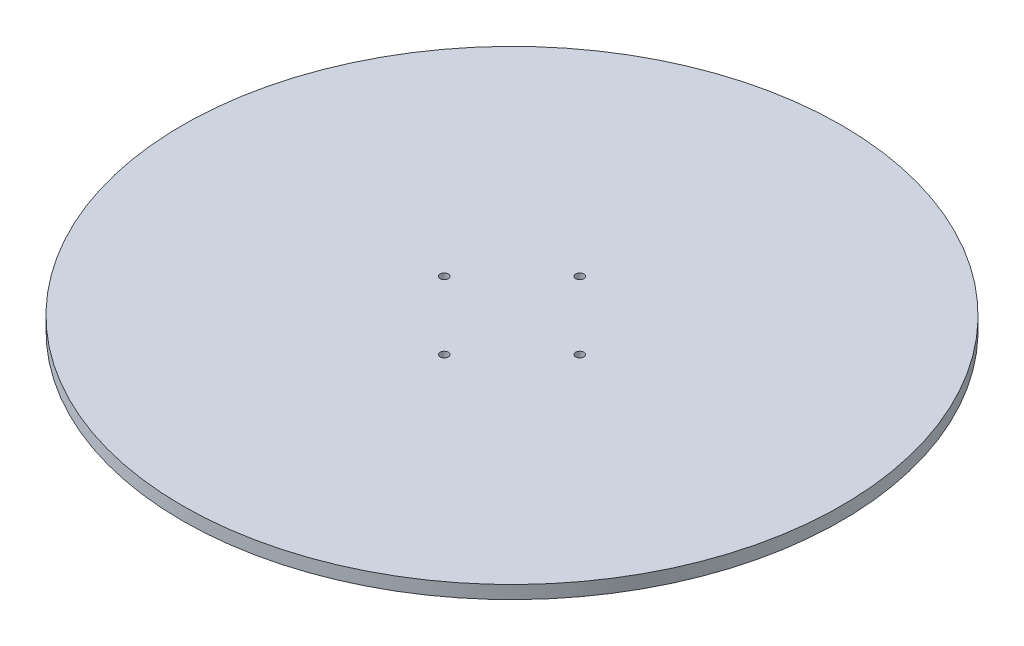
SolidWorks part; units mm, degrees
ref_plane "Front Plane" through (0, 0, 0) normal (0, 0, 1) x (1, 0, 0)
ref_plane "Top Plane" through (0, 0, 0) normal (0, 1, 0) x (1, 0, 0)
ref_plane "Right Plane" through (0, 0, 0) normal (1, 0, 0) x (0, 0, -1)
sketch "Sketch1" plane through (0, 0, 0) normal (0, 1, 0) x (1, 0, 0)
  line L5 (-40, -40) -> (40, 40) construction
  line L6 (-40, 40) -> (40, -40) construction
  circle A0 centre (0, 0) radius 80
  point P0 (0, 0)
  dimension "D3" = 160
  dimension "D1" = 80
  dimension "D2" = 80
extrude "Boss-Extrude1" add sketch "Sketch1" along normal mid plane 3.175
sketch "Sketch2" plane through (0, -1.5875, 0) normal (0, -1, 0) x (1, 0, 0)
  circle A0 centre (-16.45, 0) radius 0.85 construction
  circle A1 centre (0, -16.45) radius 0.85 construction
  circle A2 centre (0, 16.45) radius 0.85 construction
  circle A3 centre (16.45, 0) radius 0.85 construction
  circle A4 centre (-16.45, 0) radius 0.85
  circle A5 centre (0, -16.45) radius 0.85
  circle A6 centre (0, 16.45) radius 0.85
  circle A7 centre (16.45, 0) radius 0.85
  circle A8 centre (0, -16.45) radius 1
  circle A9 centre (16.45, 0) radius 1
  circle A10 centre (0, 16.45) radius 1
  circle A11 centre (-16.45, 0) radius 1
  dimension "D1" = 2
extrude "Cut-Extrude2" cut sketch "Sketch2" against normal through all contours A7 | A9 A7 | A8 A5 | A5 | A11 A4 | A4 | A10 A6 | A6
